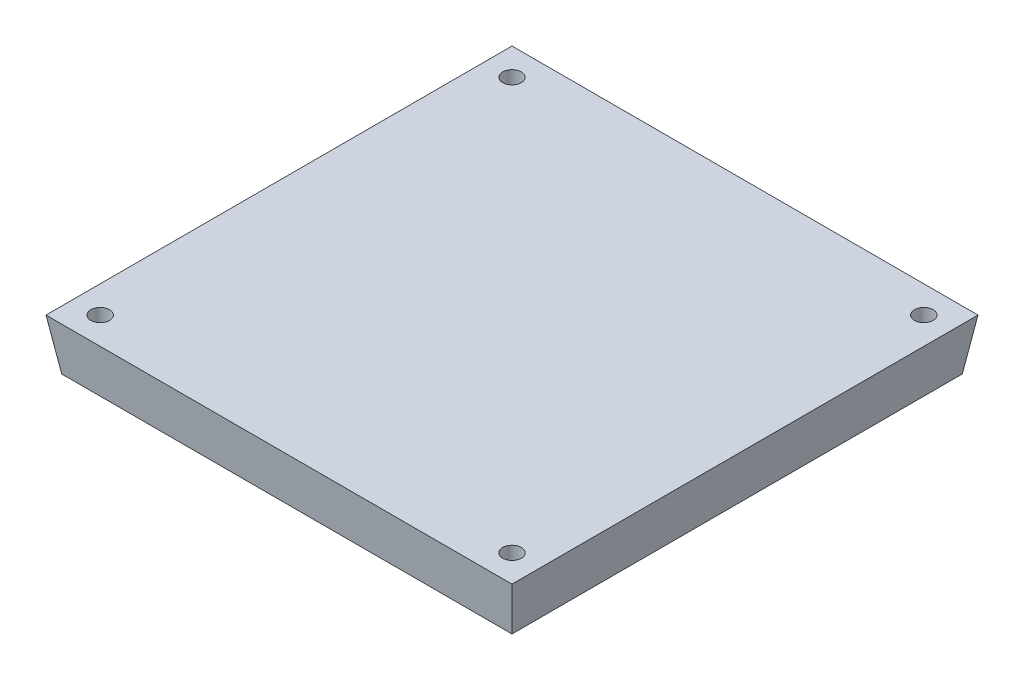
SolidWorks part; units mm, degrees
ref_plane "Front Plane" through (0, 0, 0) normal (0, 0, 1) x (1, 0, 0)
ref_plane "Top Plane" through (0, 0, 0) normal (0, 1, 0) x (1, 0, 0)
ref_plane "Right Plane" through (0, 0, 0) normal (1, 0, 0) x (0, 0, -1)
sketch "Sketch1" plane through (0, 0, 0) normal (0, 1, 0) x (1, 0, 0)
  line L1 (-36.15, 36.15) -> (36.15, 36.15)
  line L2 (-36.15, 36.15) -> (-36.15, -36.15)
  line L3 (-36.15, -36.15) -> (36.15, -36.15)
  line L4 (36.15, 36.15) -> (36.15, -36.15)
  point P0 (0, 0)
  point P6 (0, 0)
  dimension "D1" = 72.3
  dimension "D2" = 72.3
  dimension "D3" = 36.15
  dimension "D4" = 36.15
extrude "Boss-Extrude1" add sketch "Sketch1" along normal blind 8.2 draft 8.77 draft outward yes
sketch "Sketch2" plane through (0, 8.2, 0) normal (0, 1, 0) x (1, 0, 0)
  line L0 (37.415, 37.415) -> (-37.415, 37.415) construction
  line L1 (-37.415, 37.415) -> (-37.415, -37.415) construction
  circle A0 centre (-33.0666, 33.0666) radius 1.5
  circle A1 centre (33.0666, 33.0666) radius 1.5
  circle A2 centre (33.0666, -33.0666) radius 1.5
  circle A3 centre (-33.0666, -33.0666) radius 1.5
  point P15 (0, 0)
  dimension "D1" = 4.3484
  dimension "D2" = 4.3484
  dimension "D3" = 4
extrude "Cut-Extrude1" cut sketch "Sketch2" against normal blind 10
